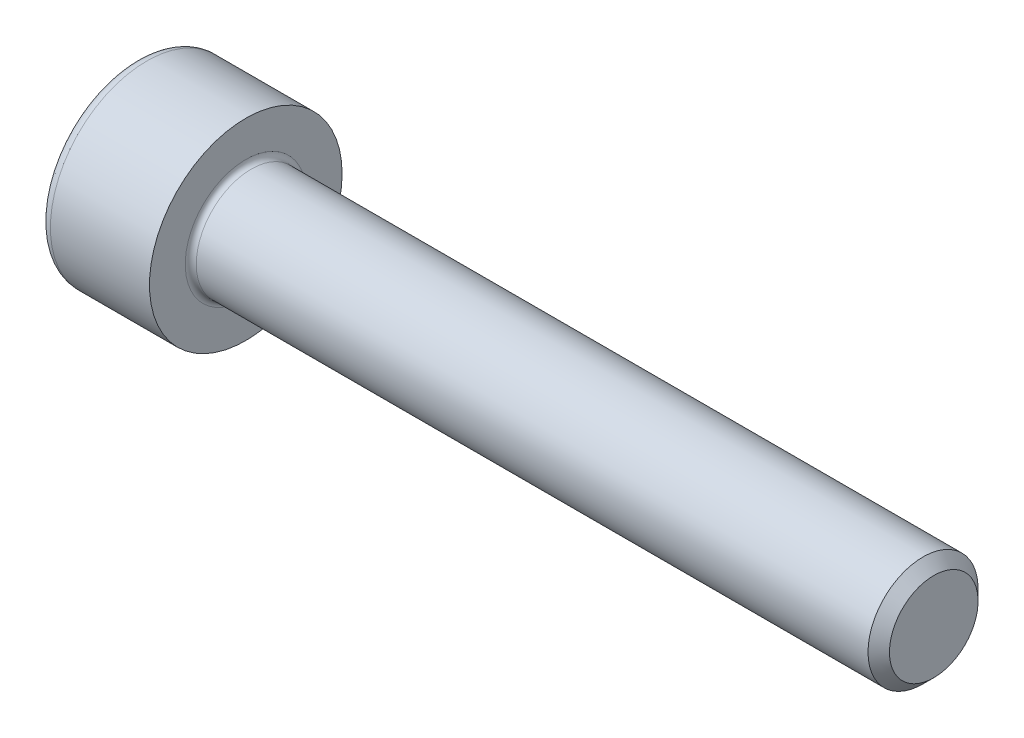
SolidWorks part; units mm, degrees
ref_plane "Front Plane" through (0, 0, 0) normal (0, 0, 1) x (1, 0, 0)
ref_plane "Top Plane" through (0, 0, 0) normal (0, 1, 0) x (1, 0, 0)
ref_plane "Right Plane" through (0, 0, 0) normal (1, 0, 0) x (0, 0, -1)
sketch "BaseHeadSke" plane through (0, 0, 0) normal (1, 0, 0) x (0, 0, -1)
  circle A1 centre (0, 0) radius 3.5
  dimension "Head_diameter" = 7
extrude "BaseHead" add sketch "BaseHeadSke" along normal blind 4
sketch "BodySke" plane through (0, 0, 0) normal (0, 0, 1) x (1, 0, 0)
  line L0 (0, 0) -> (29, 0)
  line L1 (29, 0) -> (29, 1.61)
  line L2 (29, 1.61) -> (28.61, 2)
  line L3 (28.61, 2) -> (0, 2)
  line L4 (0, 2) -> (0, 0)
  line L6 (0, 0) -> (159.3976, 0) construction
  line L7 (4, -84.3176) -> (4, 77.7215) construction
  line L8 (28.3, -21.5941) -> (28.3, 39.2994) construction
  line L10 (4, -3.5) -> (4, 3.5) construction
  dimension "Ang" = 45
  dimension "Diameter" = 4
  dimension "Minor_dia" = 3.22
  dimension "Thread_length" = 25
  dimension "Advance" = 0.7
  dimension "Length" = 25
revolve "BaseBody" add sketch "BodySke" angle 360 about L6
cosmetic thread "ThreadCosmetic" [suppressed] parameters "Thread_length"=25, "Thread_minor"=3.22
sketch "CutSocketSke" plane through (0, 0, 0) normal (1, 0, 0) x (0, 0, -1)
  line L1 (0, 1.7321) -> (-1.5, 0.866)
  line L2 (-1.5, 0.866) -> (-1.5, -0.866)
  line L3 (-1.5, -0.866) -> (0, -1.7321)
  line L4 (0, -1.7321) -> (1.5, -0.866)
  line L5 (1.5, -0.866) -> (1.5, 0.866)
  line L6 (1.5, 0.866) -> (0, 1.7321)
  circle A0 centre (0, 0) radius 1.5 construction
  dimension "Socket_width" = 3
extrude "CutSocket" cut sketch "CutSocketSke" along normal blind 2
sketch "CutHoleSke" plane through (0, 0, 0) normal (0, 0, 1) x (1, 0, 0)
  line L0 (0, 0) -> (149.4323, 0) construction
  line L1 (0, 1.5) -> (2.6, 1.5)
  line L2 (2.6, 1.5) -> (3.466, 0)
  line L3 (3.466, 0) -> (0, 0)
  line L4 (0, 0) -> (0, 1.5)
  line L6 (4, -3.5) -> (4, 3.5) construction
  dimension "D1" = 60
  dimension "Hole_depth" = 1.4
  dimension "D2" = 3
revolve "CutHole" cut sketch "CutHoleSke" angle 360 about L0
fillet "Fillet1" radius 0.2 1 edges at (4, 0, -2)
fillet "Fillet2" radius 0.4 1 edges at (0, 0, -3.5)
sketch "ThdSchSke" plane through (0, 0, 0) normal (0, 0, 1) x (1, 0, 0)
  line L0 (28.0748, 2.4503) -> (28.0748, 2)
  line L1 (28.0748, 2) -> (28.3, 1.61)
  line L2 (28.3, 1.61) -> (28.5252, 2)
  line L3 (28.5252, 2) -> (28.5252, 2.4503)
  line L4 (28.5252, 2.4503) -> (28.0748, 2.4503)
  line L6 (0, 0) -> (141.9934, 0) construction
  line L7 (29, -1.61) -> (29, 1.61) construction
  dimension "Advance" = 0.7
  dimension "D2" = 3.22
  dimension "D3" = 4
revolve "ThreadSchematic" [suppressed] cut sketch "ThdSchSke" angle 360 about L6
pattern_linear "ThdSchPat" [suppressed] count 34 spacing 0.7 along (1, 0, 0)
equation "\"Thread_minor@ThreadCosmetic\" = \"Minor_dia@BodySke\""
equation "\"Thread_length@ThreadCosmetic\" = \"Thread_length@BodySke\""
equation "\"D2@CutHoleSke\" = \"Socket_width@CutSocketSke\""
equation "\"D2@ThdSchSke\" = \"Minor_dia@BodySke\""
equation "\"D3@ThdSchSke\" = \"Diameter@BodySke\""
equation "\"Advance@ThdSchSke\" = \"Advance@BodySke\""
equation "\"D3@ThdSchPat\" = \"Advance@BodySke\""
equation "\"D1@ThdSchPat\" =  int( \"Thread_length@BodySke\"/\"Advance@BodySke\" )-1"
